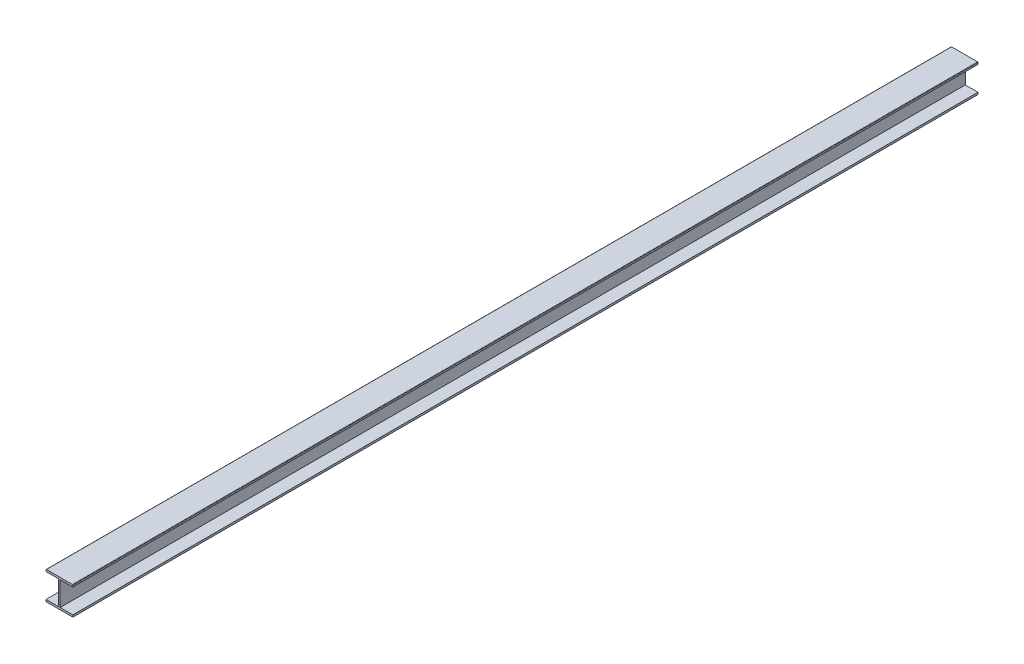
SolidWorks part; units mm, degrees
material "ASTM A992 Steel"
ref_plane "Front" through (0, 0, 0) normal (0, 0, 1) x (1, 0, 0)
ref_plane "Top" through (0, 0, 0) normal (0, 1, 0) x (1, 0, 0)
ref_plane "Right" through (0, 0, 0) normal (1, 0, 0) x (0, 0, -1)
sketch "Sketch1" plane through (0, 0, 0) normal (0, 0, 1) x (1, 0, 0)
  line L0 (0, -0.0002) -> (154.432, -0.0002)
  line L1 (154.432, -0.0002) -> (154.432, -11.5572)
  line L2 (154.432, -11.5572) -> (81.28, -11.5572)
  line L3 (81.28, -11.5572) -> (81.28, -150.4952)
  line L4 (81.28, -150.4952) -> (154.432, -150.4952)
  line L5 (154.432, -150.4952) -> (154.432, -162.0522)
  line L6 (154.432, -162.0522) -> (0, -162.0522)
  line L7 (0, -162.0522) -> (0, -150.4952)
  line L8 (0, -150.4952) -> (73.152, -150.4952)
  line L9 (73.152, -150.4952) -> (73.152, -11.5572)
  line L10 (73.152, -11.5572) -> (0, -11.5572)
  line L11 (0, -11.5572) -> (0, -0.0002)
  line L12 (77.216, -0.0002) -> (77.216, -162.0522) construction
  point P15 (154.432, -156.2737)
  dimension "D1" = 8.128
  dimension "D2" = 11.557
  dimension "D3" = 11.557
  dimension "D4" = 11.557
  dimension "D5" = 162.052
  dimension "D6" = 4.064
  dimension "D7" = 77.216
  dimension "D8" = 77.216
extrude "Boss-Extrude1" add sketch "Sketch1" along normal blind 5214.4
sketch "Sketch2" plane through (0, -162.0522, 0) normal (0, -1, 0) x (1, 0, 0)
  line L0 (0, 5214.4) -> (0, 0) construction
  line L1 (154.432, 5214.4) -> (154.432, 0) construction
  line L3 (154.432, 2607.2) -> (154.432, 2759.6)
  line L4 (154.432, 2759.6) -> (-279.5172, 2759.6)
  line L5 (-279.5172, 2607.2) -> (-279.5172, 2759.6)
  line L8 (154.432, 2607.2) -> (154.432, 2454.8)
  line L9 (154.432, 2454.8) -> (-279.5172, 2454.8)
  line L10 (-279.5172, 2607.2) -> (-279.5172, 2454.8)
  point P0 (0, 2607.2)
  dimension "D1" = 152.4
  dimension "D2" = 152.4
split line "Split Line1"
sketch "Sketch3" plane through (0, -162.0522, 0) normal (0, -1, 0) x (1, 0, 0)
  line L0 (154.432, 5214.4) -> (154.432, 2759.6) construction
  line L1 (0, 5214.4) -> (154.432, 5214.4)
  line L2 (0, 5214.4) -> (0, 4909.6)
  line L3 (0, 4909.6) -> (154.432, 4909.6)
  line L4 (154.432, 5214.4) -> (154.432, 4909.6)
  line L5 (154.432, 2454.8) -> (154.432, 0) construction
  line L6 (0, 0) -> (154.432, 0)
  line L7 (0, 0) -> (0, 304.8)
  line L8 (0, 304.8) -> (154.432, 304.8)
  line L9 (154.432, 0) -> (154.432, 304.8)
  dimension "D1" = 304.8
  dimension "D2" = 304.8
split line "Split Line2"
fillet "Fillet1" radius 2.54 2 edges at (154.432, -0.0002, 2607.2) (0, -0.0002, 2607.2)
